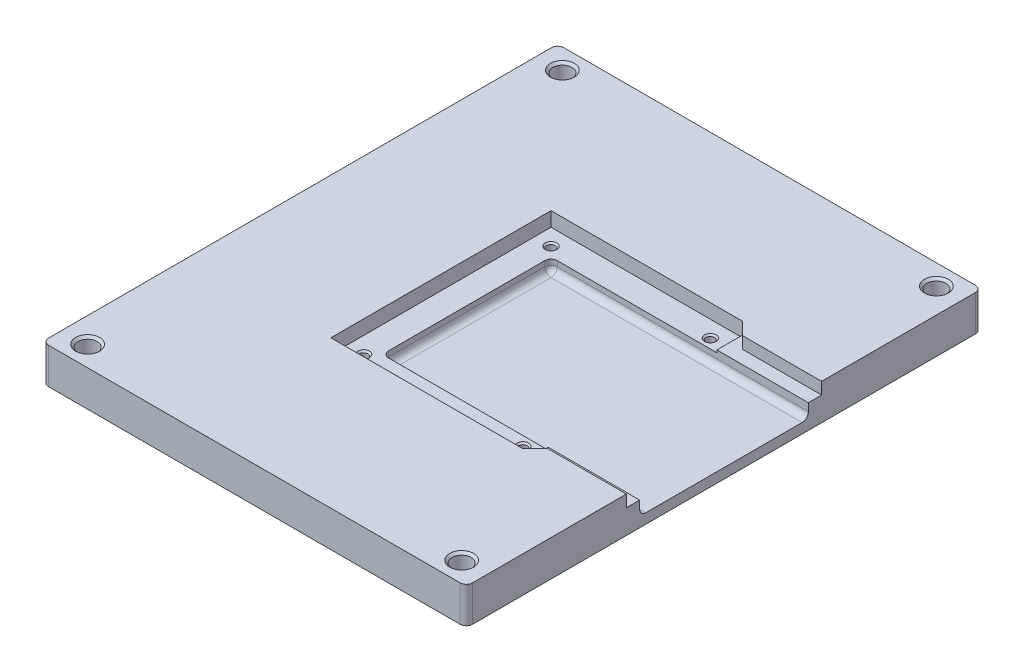
SolidWorks part; units mm, degrees
ref_plane "Front Plane" through (0, 0, 0) normal (0, 0, 1) x (1, 0, 0)
ref_plane "Top Plane" through (0, 0, 0) normal (0, 1, 0) x (1, 0, 0)
ref_plane "Right Plane" through (0, 0, 0) normal (1, 0, 0) x (0, 0, -1)
sketch "Sketch1" plane through (0, 0, 0) normal (0, 1, 0) x (1, 0, 0)
  line L0 (0, -67.5) -> (0, 67.5) construction
  line L1 (67.875, 67.5) -> (-67.875, 67.5) construction
  line L2 (-67.875, 67.5) -> (-67.875, -67.5)
  line L3 (-67.875, 0) -> (67.875, 0) construction
  line L4 (-67.875, 67.5) -> (-67.875, 80.5)
  line L5 (-65.875, 82.5) -> (65.875, 82.5)
  line L6 (0, 82.5) -> (0, 67.5) construction
  line L7 (67.875, 67.5) -> (67.875, 80.5)
  line L8 (67.875, 67.5) -> (67.875, -67.5)
  line L9 (0, -82.5) -> (0, -67.5) construction
  line L10 (67.875, -67.5) -> (-67.875, -67.5) construction
  line L11 (67.875, -67.5) -> (67.875, -80.5)
  line L12 (-65.875, -82.5) -> (65.875, -82.5)
  line L13 (-67.875, -67.5) -> (-67.875, -80.5)
  line L14 (-67.875, 70.5) -> (67.875, 70.5) construction
  circle A1 centre (-59.875, 76) radius 3.075 construction
  circle A2 centre (59.875, 76) radius 3.075 construction
  circle A5 centre (59.875, -76) radius 3.075 construction
  circle A6 centre (-59.875, -76) radius 3.075 construction
  arc A8 (-65.875, -82.5) -> (-67.875, -80.5) centre (-65.875, -80.5) cw
  arc A9 (67.875, -80.5) -> (65.875, -82.5) centre (65.875, -80.5) cw
  arc A10 (67.875, 80.5) -> (65.875, 82.5) centre (65.875, 80.5) ccw
  arc A11 (-67.875, 80.5) -> (-65.875, 82.5) centre (-65.875, 80.5) cw
  point P24 (0, 0)
  point P36 (-67.875, -82.5)
  point P39 (67.875, -82.5)
  point P42 (67.875, 82.5)
  point P45 (-67.875, 82.5)
  dimension "D10" = 2
  dimension "D3" = 6.15
  dimension "D1" = 67.875
  dimension "D2" = 67.5
  dimension "D4" = 6.5
  dimension "D6" = 8
  dimension "D7" = 8.5
  dimension "D8" = 12
  dimension "D9" = 3
  dimension "D11" = 82.5
extrude "Boss-Extrude1" add sketch "Sketch1" along normal blind 11.5
sketch "Sketch3" plane through (0, 11.5, 0) normal (0, 1, 0) x (1, 0, 0)
  line L0 (0, 0) -> (-67.875, 0) construction
  line L1 (-67.875, 80.5) -> (-67.875, -80.5) construction
  line L2 (0, 0) -> (0, 82.5) construction
  line L3 (65.875, 82.5) -> (-65.875, 82.5) construction
  line L4 (3.96, -16.3) -> (3.96, 16.3)
  line L5 (-2.46, -17.8) -> (2.46, -17.8)
  line L6 (-3.96, 16.3) -> (-3.96, -16.3)
  line L7 (2.46, 17.8) -> (-2.46, 17.8)
  line L8 (0, 17.8) -> (0, -17.8) construction
  line L9 (13.25, 0) -> (0, 0) construction
  line L10 (16.15, 10.025) -> (10.35, 10.025)
  line L11 (16.15, 10.025) -> (16.15, -10.025)
  line L12 (16.15, -10.025) -> (10.35, -10.025)
  line L13 (10.35, 10.025) -> (10.35, -10.025)
  line L14 (16.15, 10.025) -> (10.35, -10.025) construction
  line L15 (16.15, -10.025) -> (10.35, 10.025) construction
  line L16 (13.25, 0) -> (13.25, 10.025) construction
  line L17 (-16.15, 10.025) -> (-16.15, -10.025)
  line L18 (-16.15, -10.025) -> (-10.35, -10.025)
  line L23 (-16.15, 10.025) -> (-10.35, 10.025)
  line L24 (-10.35, 10.025) -> (-10.35, -10.025)
  arc A0 (-2.46, 17.8) -> (-3.96, 16.3) centre (-2.46, 16.3) ccw
  arc A1 (3.96, 16.3) -> (2.46, 17.8) centre (2.46, 16.3) ccw
  arc A2 (2.46, -17.8) -> (3.96, -16.3) centre (2.46, -16.3) ccw
  arc A3 (-3.96, -16.3) -> (-2.46, -17.8) centre (-2.46, -16.3) ccw
  point P9 (0, 0)
  point P23 (0, 0)
  dimension "D2" = 1.5
  dimension "D1" = 35.6
  dimension "D3" = 7.92
  dimension "D4" = 20.05
  dimension "D5" = 5.8
  dimension "D6" = 13.25
sketch "Sketch4" plane through (0, 11.5, 0) normal (0, 1, 0) x (1, 0, 0)
  circle A0 centre (-59.875, -76) radius 3.075 construction
  circle A1 centre (59.875, -76) radius 3.075 construction
  circle A2 centre (59.875, 76) radius 3.075 construction
  circle A5 centre (-59.875, 76) radius 3.075 construction
  circle A8 centre (-59.875, -76) radius 3.075
  circle A9 centre (59.875, -76) radius 3.075
  circle A10 centre (59.875, 76) radius 3.075
  circle A13 centre (-59.875, 76) radius 3.075
extrude "Cut-Extrude1" cut sketch "Sketch4" against normal blind 6
sketch "Sketch21" plane through (0, 11.5, 0) normal (0, 1, 0) x (1, 0, 0)
  line L0 (38.5, 35) -> (-22.5, 35) construction
  line L1 (38.5, 35) -> (42.5, 31) construction
  line L2 (-22.5, 35) -> (-22.5, -35) construction
  line L3 (-22.5, 0) -> (0, 0) construction
  line L4 (0, 0) -> (38.5, 0) construction
  line L5 (38.5, -35) -> (38.5, 35) construction
  line L6 (38.5, -35) -> (-22.5, -35) construction
  line L7 (42.5, 31) -> (67.875, 31) construction
  line L8 (67.875, -80.5) -> (67.875, 80.5) construction
  line L9 (67.875, 31) -> (67.875, -31)
  line L10 (67.875, 0) -> (38.5, 0) construction
  line L11 (42.5, -31) -> (67.875, -31) construction
  line L12 (38.5, -35) -> (42.5, -31) construction
  line L13 (42.6036, 31.25) -> (67.875, 31.25)
  line L14 (38.6036, 35.25) -> (42.6036, 31.25)
  line L15 (38.6036, 35.25) -> (-22.75, 35.25)
  line L16 (-22.75, 35.25) -> (-22.75, -35.25)
  line L17 (38.6036, -35.25) -> (-22.75, -35.25)
  line L18 (38.6036, -35.25) -> (42.6036, -31.25)
  line L19 (42.6036, -31.25) -> (67.875, -31.25)
  line L20 (67.875, -31.25) -> (67.875, -31)
  line L21 (67.875, 31) -> (67.875, 31.25)
  circle A0 centre (-17.5, 30) radius 1.6 construction
  circle A1 centre (33.5, 30) radius 1.6 construction
  circle A2 centre (33.5, -30) radius 1.6 construction
  circle A3 centre (-17.5, -30) radius 1.6 construction
  dimension "D8" = 3.2
  dimension "D1" = 22.5
  dimension "D2" = 61
  dimension "D3" = 35
  dimension "D4" = 5
  dimension "D5" = 5
  dimension "D6" = 5
  dimension "D7" = 5
  dimension "D9" = 45
  dimension "D10" = 4
  dimension "D12" = 25.375
  dimension "D11" = 0.25
extrude "Cut-Extrude6" cut sketch "Sketch21" against normal blind 4.6
sketch "Sketch24" plane through (0, 6.9, 0) normal (0, 1, 0) x (1, 0, 0)
  line L0 (67.875, 27) -> (-14.5, 27)
  line L2 (-14.5, 27) -> (-14.5, -27)
  line L3 (-14.5, -27) -> (67.875, -27)
  line L4 (67.875, -27) -> (67.875, 27)
  line L8 (38.5, 35) -> (-22.5, 35) construction
  line L10 (-22.5, 35) -> (-22.5, -35) construction
  line L11 (38.5, -35) -> (-22.5, -35) construction
  line L12 (67.875, -31.25) -> (67.875, 31.25) construction
  dimension "D1" = 8
  dimension "D2" = 8
  dimension "D3" = 8
extrude "Cut-Extrude3" cut sketch "Sketch24" against normal blind 3.7 and the other way through all
sketch "Sketch25" plane through (0, 6.9, 0) normal (0, 1, 0) x (1, 0, 0)
  circle A0 centre (33.5, 30) radius 1.35
  circle A1 centre (-17.5, 30) radius 1.35
  circle A2 centre (33.5, -30) radius 1.35
  circle A3 centre (-17.5, -30) radius 1.35
  dimension "D1" = 2.7
extrude "Cut-Extrude4" cut sketch "Sketch25" against normal blind 5
chamfer "Chamfer4" distance 0.5 angle 45 4 edges at (-17.5, 6.9, 31.35) (33.5, 6.9, 31.35) (33.5, 6.9, -28.65) (-17.5, 6.9, -28.65)
fillet "Fillet1" radius 2 5 edges at (26.6875, 3.2, 27) (-14.5, 5.05, 27) (-14.5, 5.05, -27) (-14.5, 3.2, 0) (26.6875, 3.2, -27)
sketch "Sketch26" plane through (0, 6.9, 0) normal (0, 1, 0) x (1, 0, 0)
  line L0 (0, 0) -> (67.875, 0) construction
  line L1 (67.875, -25) -> (67.875, 25) construction
  line L2 (38.6036, 35.25) -> (38.6036, 27)
  line L3 (67.875, 27) -> (-12.5, 27) construction
  line L4 (38.6036, 27) -> (67.875, 27)
  line L5 (67.875, 27) -> (67.875, 31.25)
  line L6 (67.875, 31.25) -> (42.6036, 31.25)
  line L7 (42.6036, 31.25) -> (38.6036, 35.25)
  line L8 (42.6036, -31.25) -> (38.6036, -35.25)
  line L9 (67.875, -31.25) -> (42.6036, -31.25)
  line L10 (67.875, -27) -> (67.875, -31.25)
  line L11 (38.6036, -27) -> (67.875, -27)
  line L12 (38.6036, -35.25) -> (38.6036, -27)
extrude "Boss-Extrude2" add sketch "Sketch26" along normal blind 0.8
chamfer "Chamfer5" distance 0.75 angle 45 4 edges at (59.875, 11.5, 79.075) (-59.875, 11.5, 79.075) (-59.875, 11.5, -72.925) (59.875, 11.5, -72.925)
equation "\"D5@Sketch21\"=\"D4@Sketch21\""
equation "\"D6@Sketch21\"=\"D4@Sketch21\""
equation "\"D7@Sketch21\"=\"D4@Sketch21\""
equation "\"D2@Sketch24\"=\"D1@Sketch24\""
equation "\"D3@Sketch24\"=\"D1@Sketch24\""
